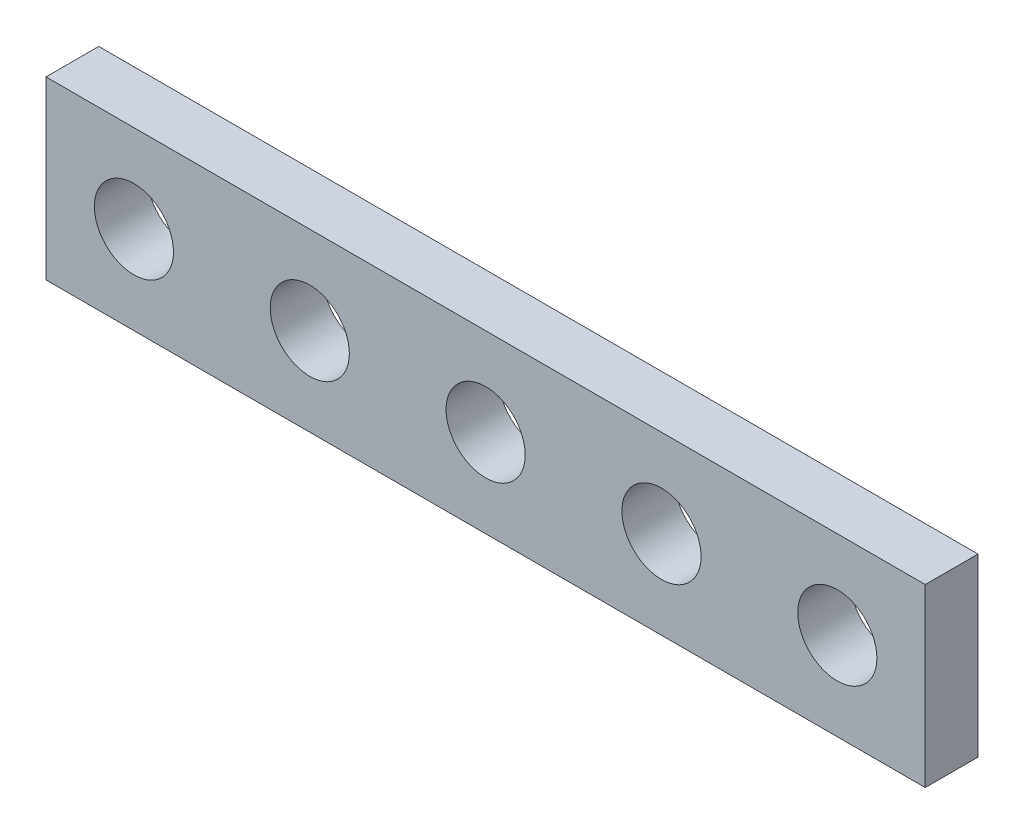
SolidWorks part; units mm, degrees
ref_plane "Alzado" through (0, 0, 0) normal (0, 0, 1) x (1, 0, 0)
ref_plane "Planta" through (0, 0, 0) normal (0, 1, 0) x (1, 0, 0)
ref_plane "Vista lateral" through (0, 0, 0) normal (1, 0, 0) x (0, 0, -1)
sketch "Croquis1" plane through (0, 0, 0) normal (0, 0, 1) x (1, 0, 0)
  line L0 (0, 0) -> (0, 10)
  line L1 (0, 10) -> (50, 10)
  line L2 (50, 10) -> (50, 0)
  line L3 (50, 0) -> (0, 0)
  dimension "D1" = 10
  dimension "D2" = 50
extrude "Saliente-Extruir1" add sketch "Croquis1" along normal blind 3
sketch "Croquis2" plane through (0, 0, 3) normal (0, 0, 1) x (1, 0, 0)
  line L0 (0, 5) -> (50, 5) construction
  line L1 (0, 10) -> (0, 0) construction
  line L2 (50, 0) -> (50, 10) construction
  line L3 (25, 10) -> (25, 0) construction
  line L4 (50, 10) -> (0, 10) construction
  line L5 (0, 0) -> (50, 0) construction
  circle A0 centre (5, 5) radius 2.25
  circle A1 centre (15, 5) radius 2.25
  circle A2 centre (25, 5) radius 2.25
  circle A3 centre (35, 5) radius 2.25
  circle A4 centre (45, 5) radius 2.25
  point P22 (0, 0)
  point P23 (25, 5)
  point P24 (0, 0)
  point P25 (0, 0)
  point P26 (0, 0)
  point P27 (0, 0)
  dimension "D5" = 4.5
  dimension "D1" = 10
  dimension "D2" = 10
  dimension "D3" = 10
  dimension "D4" = 10
extrude "Cortar-Extruir1" cut sketch "Croquis2" against normal through all
